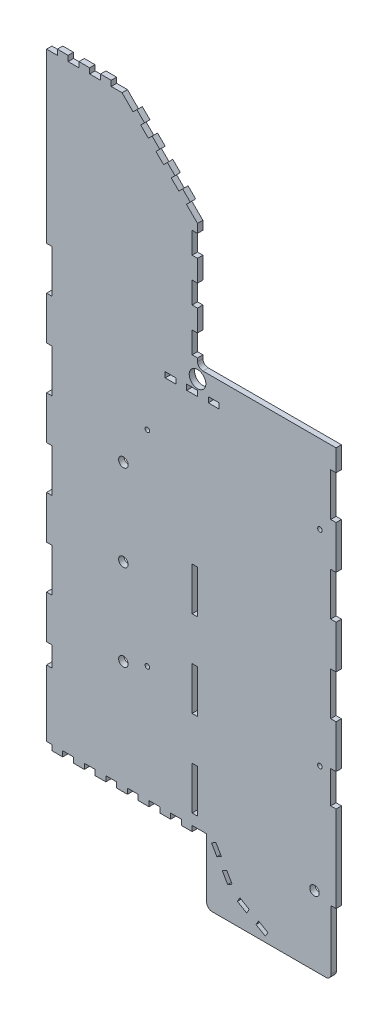
SolidWorks part; units mm, degrees
material "Acrylic (Medium-high impact)"
ref_plane "Front Plane" through (0, 0, 0) normal (0, 0, 1) x (1, 0, 0)
ref_plane "Top Plane" through (0, 0, 0) normal (0, 1, 0) x (1, 0, 0)
ref_plane "Right Plane" through (0, 0, 0) normal (1, 0, 0) x (0, 0, -1)
sketch "Sketch1" plane through (0, 0, 0) normal (0, 0, 1) x (1, 0, 0)
  line L0 (0, 3.175) -> (3.175, 3.175)
  line L1 (3.175, 3.175) -> (3.175, 0)
  line L2 (3.175, 0) -> (9.525, 0)
  line L3 (9.525, 0) -> (9.525, 3.175)
  line L4 (9.525, 3.175) -> (15.875, 3.175)
  line L5 (15.875, 3.175) -> (15.875, 0)
  line L6 (15.875, 0) -> (22.225, 0)
  line L7 (22.225, 0) -> (22.225, 3.175)
  line L8 (22.225, 3.175) -> (28.575, 3.175)
  line L9 (28.575, 3.175) -> (28.575, 0)
  line L10 (28.575, 0) -> (34.925, 0)
  line L11 (34.925, 0) -> (34.925, 3.175)
  line L12 (34.925, 3.175) -> (41.275, 3.175)
  line L13 (41.275, 3.175) -> (41.275, 0)
  line L14 (41.275, 0) -> (47.625, 0)
  line L15 (47.625, 0) -> (47.625, 3.175)
  line L16 (47.625, 3.175) -> (53.975, 3.175)
  line L17 (53.975, 3.175) -> (53.975, 0)
  line L18 (53.975, 0) -> (60.325, 0)
  line L19 (60.325, 0) -> (60.325, 3.175)
  line L20 (60.325, 3.175) -> (66.675, 3.175)
  line L21 (66.675, 3.175) -> (66.675, 0)
  line L22 (66.675, 0) -> (73.025, 0)
  line L23 (73.025, 0) -> (73.025, 3.175)
  line L24 (73.025, 3.175) -> (79.375, 3.175)
  line L25 (79.375, 3.175) -> (79.375, 0)
  line L26 (79.375, 0) -> (85.725, 0)
  line L27 (85.725, 0) -> (85.725, 3.175)
  line L28 (85.725, 3.175) -> (88.9, 3.175)
  line L29 (0, 3.175) -> (0, 28.575)
  line L30 (0, 356.235) -> (6.35, 356.235)
  line L31 (88.9, 311.785) -> (88.9, 306.705)
  line L32 (0, 28.575) -> (3.175, 28.575) construction
  line L33 (3.175, 28.575) -> (3.175, 53.975) construction
  line L34 (3.175, 53.975) -> (0, 53.975)
  line L35 (0, 79.375) -> (3.175, 79.375)
  line L36 (3.175, 79.375) -> (3.175, 104.775)
  line L37 (3.175, 104.775) -> (0, 104.775)
  line L38 (0, 130.175) -> (3.175, 130.175)
  line L39 (3.175, 130.175) -> (3.175, 155.575)
  line L40 (3.175, 155.575) -> (0, 155.575)
  line L41 (0, 180.975) -> (3.175, 180.975)
  line L42 (3.175, 180.975) -> (3.175, 206.375)
  line L43 (3.175, 206.375) -> (0, 206.375)
  line L44 (0, 231.775) -> (3.175, 231.775)
  line L45 (3.175, 231.775) -> (3.175, 257.175)
  line L46 (3.175, 257.175) -> (0, 257.175)
  line L47 (0, 257.175) -> (0, 356.235)
  line L48 (0, 206.375) -> (0, 231.775)
  line L49 (0, 155.575) -> (0, 180.975)
  line L50 (0, 104.775) -> (0, 130.175)
  line L51 (0, 53.975) -> (0, 79.375)
  line L52 (44.45, 356.235) -> (50.9596, 349.7254)
  line L53 (88.9, 20.278) -> (120.7715, -34.925) construction
  line L54 (85.725, 111.125) -> (88.9, 111.125)
  line L55 (85.725, 111.125) -> (85.725, 136.525)
  line L56 (85.725, 136.525) -> (88.9, 136.525)
  line L57 (88.9, 111.125) -> (88.9, 136.525)
  line L58 (110.9837, -17.9721) -> (140.347, -34.925) construction
  line L59 (99.7423, 1.4986) -> (102.9173, -4.0007)
  line L60 (102.9173, -4.0007) -> (100.3217, -5.4993)
  line L61 (170.4848, 225.425) -> (167.3098, 225.425)
  line L62 (85.725, 85.725) -> (88.9, 85.725)
  line L63 (85.725, 85.725) -> (85.725, 60.325)
  line L64 (85.725, 60.325) -> (88.9, 60.325)
  line L65 (88.9, 85.725) -> (88.9, 60.325)
  line L66 (85.725, 34.925) -> (88.9, 34.925)
  line L67 (85.725, 34.925) -> (85.725, 9.525)
  line L68 (85.725, 9.525) -> (88.9, 9.525)
  line L69 (88.9, 34.925) -> (88.9, 9.525)
  line L70 (167.3098, 225.425) -> (167.3098, 200.025)
  line L71 (167.3098, 200.025) -> (170.4848, 200.025)
  line L72 (170.4848, 174.625) -> (167.3098, 174.625)
  line L73 (167.3098, 174.625) -> (167.3098, 149.225)
  line L74 (167.3098, 149.225) -> (170.4848, 149.225)
  line L75 (170.4848, 123.825) -> (167.3098, 123.825)
  line L76 (167.3098, 123.825) -> (167.3098, 98.425)
  line L77 (167.3098, 98.425) -> (170.4848, 98.425)
  line L78 (170.4848, 225.425) -> (170.4848, 238.125)
  line L79 (170.4848, 174.625) -> (170.4848, 200.025)
  line L80 (88.9, 3.175) -> (94.2848, 3.175)
  line L81 (170.4848, 3.175) -> (170.4848, 53.975)
  line L82 (170.4848, 238.125) -> (88.9, 238.125)
  line L83 (170.4848, 3.175) -> (170.4848, -34.925) construction
  line L84 (170.4848, -34.925) -> (167.5356, -34.925) construction
  line L85 (94.2848, -34.925) -> (94.2848, 3.175)
  line L86 (88.9, 311.785) -> (0, 311.785) construction
  line L87 (6.35, 356.235) -> (6.35, 359.41)
  line L88 (6.35, 359.41) -> (12.7, 359.41)
  line L89 (12.7, 359.41) -> (12.7, 356.235)
  line L90 (19.05, 356.235) -> (19.05, 359.41)
  line L91 (19.05, 359.41) -> (25.4, 359.41)
  line L92 (25.4, 359.41) -> (25.4, 356.235)
  line L93 (12.7, 356.235) -> (19.05, 356.235)
  line L94 (25.4, 356.235) -> (31.75, 356.235)
  line L95 (31.75, 356.235) -> (31.75, 359.41)
  line L96 (31.75, 359.41) -> (38.1, 359.41)
  line L97 (38.1, 359.41) -> (38.1, 356.235)
  line L98 (38.1, 356.235) -> (44.45, 356.235)
  line L99 (50.9596, 349.7254) -> (53.2046, 351.9705)
  line L100 (53.2046, 351.9705) -> (57.6947, 347.4804)
  line L101 (57.6947, 347.4804) -> (55.4497, 345.2353)
  line L102 (59.9398, 340.7452) -> (62.1849, 342.9903)
  line L103 (62.1849, 342.9903) -> (66.675, 338.5001)
  line L104 (66.675, 338.5001) -> (64.4299, 336.2551)
  line L105 (68.9201, 331.7649) -> (71.1651, 334.01)
  line L106 (71.1651, 334.01) -> (75.6553, 329.5199)
  line L107 (75.6553, 329.5199) -> (73.4102, 327.2748)
  line L108 (77.9003, 322.7847) -> (80.1454, 325.0297)
  line L109 (80.1454, 325.0297) -> (84.6355, 320.5396)
  line L110 (84.6355, 320.5396) -> (82.3904, 318.2946)
  line L111 (55.4497, 345.2353) -> (59.9398, 340.7452)
  line L112 (64.4299, 336.2551) -> (68.9201, 331.7649)
  line L113 (73.4102, 327.2748) -> (77.9003, 322.7847)
  line L114 (82.3904, 318.2946) -> (88.9, 311.785)
  line L115 (170.4848, 123.825) -> (170.4848, 149.225)
  line L116 (0, 28.575) -> (0, 42.175)
  line L117 (69.85, 226.66) -> (76.2, 226.66)
  line L118 (69.85, 226.66) -> (69.85, 223.485)
  line L119 (69.85, 223.485) -> (76.2, 223.485)
  line L120 (76.2, 226.66) -> (76.2, 223.485)
  line L121 (82.55, 223.485) -> (88.9, 223.485)
  line L122 (82.55, 223.485) -> (82.55, 226.66)
  line L123 (82.55, 226.66) -> (88.9, 226.66)
  line L124 (88.9, 223.485) -> (88.9, 226.66)
  line L125 (95.25, 226.66) -> (101.6, 226.66)
  line L126 (95.25, 226.66) -> (95.25, 223.485)
  line L127 (95.25, 223.485) -> (101.6, 223.485)
  line L128 (101.6, 226.66) -> (101.6, 223.485)
  line L129 (0, 42.175) -> (3.175, 42.175)
  line L130 (3.175, 42.175) -> (3.175, 53.975)
  line L131 (100.3217, -5.4993) -> (97.1467, 0)
  line L132 (97.1467, 0) -> (99.7423, 1.4986)
  line L133 (106.0923, -9.4999) -> (103.4967, -10.9985)
  line L134 (103.4967, -10.9985) -> (106.6717, -16.4978)
  line L135 (106.6717, -16.4978) -> (109.2673, -14.9992)
  line L136 (106.0923, -9.4999) -> (109.2673, -14.9992)
  line L137 (113.8542, -19.6293) -> (112.3556, -22.225)
  line L138 (112.3556, -22.225) -> (117.8548, -25.4)
  line L139 (117.8548, -25.4) -> (119.3534, -22.8043)
  line L140 (113.8542, -19.6293) -> (119.3534, -22.8043)
  line L141 (124.8527, -25.9793) -> (123.3541, -28.575)
  line L142 (123.3541, -28.575) -> (128.8534, -31.75)
  line L143 (128.8534, -31.75) -> (130.352, -29.1543)
  line L144 (130.352, -29.1543) -> (124.8527, -25.9793)
  line L145 (170.4848, 73.025) -> (167.3098, 73.025)
  line L146 (167.3098, 73.025) -> (167.3098, 53.975)
  line L147 (167.3098, 53.975) -> (170.4848, 53.975)
  line L148 (170.4848, 98.425) -> (170.4848, 73.025)
  line L149 (88.9, 306.705) -> (85.725, 306.705)
  line L150 (85.725, 306.705) -> (85.725, 294.005)
  line L151 (85.725, 294.005) -> (88.9, 294.005)
  line L152 (88.9, 281.305) -> (85.725, 281.305)
  line L153 (85.725, 281.305) -> (85.725, 268.605)
  line L154 (85.725, 268.605) -> (88.9, 268.605)
  line L155 (88.9, 255.905) -> (85.725, 255.905)
  line L156 (85.725, 255.905) -> (85.725, 243.205)
  line L157 (85.725, 243.205) -> (88.9, 243.205)
  line L158 (88.9, 294.005) -> (88.9, 281.305)
  line L159 (88.9, 268.605) -> (88.9, 255.905)
  line L160 (88.9, 243.205) -> (88.9, 238.125)
  line L161 (167.5356, -34.925) -> (167.5356, 3.175)
  line L162 (167.5356, 3.175) -> (170.4848, 3.175)
  line L163 (167.5356, -34.925) -> (94.2848, -34.925)
  circle A0 centre (88.9, 232.41) radius 4.8895
  circle A1 centre (59.3598, 191.77) radius 1.3335
  circle A2 centre (59.3598, 71.12) radius 1.3335
  circle A3 centre (160.9598, 71.12) radius 1.3335
  circle A4 centre (160.9598, 191.77) radius 1.3335
  circle A5 centre (157.7848, 5.969) radius 2.794
  circle A6 centre (45.225, 66.575) radius 2.794
  circle A7 centre (45.225, 117.375) radius 2.794
  circle A8 centre (45.225, 168.175) radius 2.794
  point P164 (170.4848, 41.529)
  dimension "D13" = 9.779
  dimension "D20" = 2.667
  dimension "D34" = 2.9972
  dimension "D40" = 5.588
  dimension "D1" = 3.175
  dimension "D2" = 3.175
  dimension "D3" = 6.35
  dimension "D4" = 3.175
  dimension "D5" = 353.06
  dimension "D6" = 25.4
  dimension "D7" = 25.4
  dimension "D8" = 5
  dimension "D9" = 73.66
  dimension "D10" = 25.4
  dimension "D11" = 234.95
  dimension "D12" = 81.5848
  dimension "D14" = 5.715
  dimension "D15" = 38.1
  dimension "D16" = 76.2
  dimension "D17" = 44.45
  dimension "D18" = 45
  dimension "D19" = 4
  dimension "D21" = 101.6
  dimension "D22" = 120.65
  dimension "D24" = 6.35
  dimension "D25" = 25.4
  dimension "D26" = 25.4
  dimension "D27" = 6.35
  dimension "D28" = 25.4
  dimension "D29" = 3.175
  dimension "D30" = 25.4
  dimension "D31" = 12.7
  dimension "D33" = 25.4
  dimension "D23" = 40.64
  dimension "D35" = 6.35
  dimension "D36" = 6.35
  dimension "D37" = 5.75
  dimension "D38" = 40.5
  dimension "D39" = 63.4
  dimension "D42" = 50.8
  dimension "D43" = 39
  dimension "D44" = 6.35
  dimension "D45" = 6.35
  dimension "D46" = 6.35
  dimension "D47" = 30
  dimension "D48" = 30
  dimension "D49" = 76.454
  dimension "D50" = 81.28
  dimension "D51" = 81.28
  dimension "D52" = 3.175
  dimension "D53" = 3.175
  dimension "D54" = 19.05
  dimension "D55" = 12.7
  dimension "D56" = 3.175
  dimension "D57" = 2.794
  dimension "D58" = 12.7
  dimension "D60" = 2.9492
  dimension "D32" = 3
  dimension "D41" = 3
extrude "Boss-Extrude2" add sketch "Sketch1" along normal blind 3.175
fillet "Fillet1" radius 3.175 3 edges at (88.9, 238.125, 1.5875) (167.5356, -34.925, 1.5875) (94.2848, -34.925, 1.5875)
